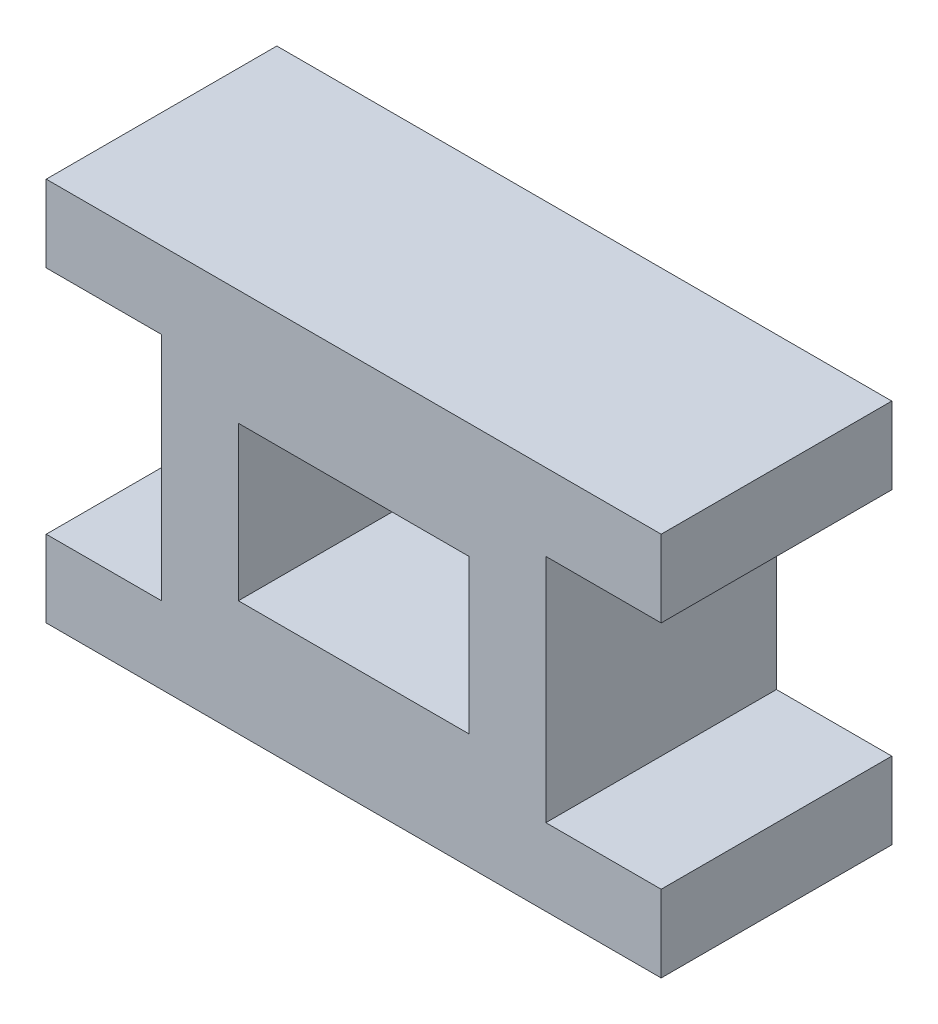
SolidWorks part; units mm, degrees
ref_plane "Front Plane" through (0, 0, 0) normal (0, 0, 1) x (1, 0, 0)
ref_plane "Top Plane" through (0, 0, 0) normal (0, 1, 0) x (1, 0, 0)
ref_plane "Right Plane" through (0, 0, 0) normal (1, 0, 0) x (0, 0, -1)
sketch "Sketch1" plane through (0, 0, 0) normal (0, 0, 1) x (1, 0, 0)
  line L0 (0, 0) -> (37001.9817, 0) construction
  line L1 (0, 0) -> (0, 37001.9817) construction
  line L2 (25, 40.625) -> (25, 9.375)
  line L3 (-40, 50) -> (40, 50)
  line L4 (-40, 50) -> (-40, 40)
  line L5 (-40, 0) -> (40, 0)
  line L6 (40, 50) -> (40, 40)
  line L7 (-40, 50) -> (40, 0) construction
  line L8 (-40, 0) -> (40, 50) construction
  line L9 (-15, 35) -> (15, 35)
  line L10 (-15, 35) -> (-15, 15)
  line L11 (-15, 15) -> (15, 15)
  line L12 (15, 35) -> (15, 15)
  line L13 (-15, 35) -> (15, 15) construction
  line L14 (-15, 15) -> (15, 35) construction
  line L15 (40, 40) -> (25, 40)
  line L16 (40, 10) -> (25, 10)
  line L17 (40, 10) -> (40, 0)
  line L18 (40, 0) -> (-40, 50) construction
  line L19 (40, 50) -> (-40, 0) construction
  line L20 (-40, 10) -> (-40, 0)
  line L21 (-40, 10) -> (-25, 10)
  line L22 (-40, 40) -> (-25, 40)
  line L23 (-40, 50) -> (-40, 40)
  line L24 (-25, 40.625) -> (-25, 9.375)
  line L25 (-40, 10) -> (-40, 0)
  point P5 (0, 25)
  point P10 (0, 25)
  dimension "D1" = 80
  dimension "D2" = 50
  dimension "D3" = 30
  dimension "D4" = 15
  dimension "D5" = 10
  dimension "D6" = 10
  dimension "D7" = 10
extrude "Boss-Extrude1" add sketch "Sketch1" along normal blind 30
